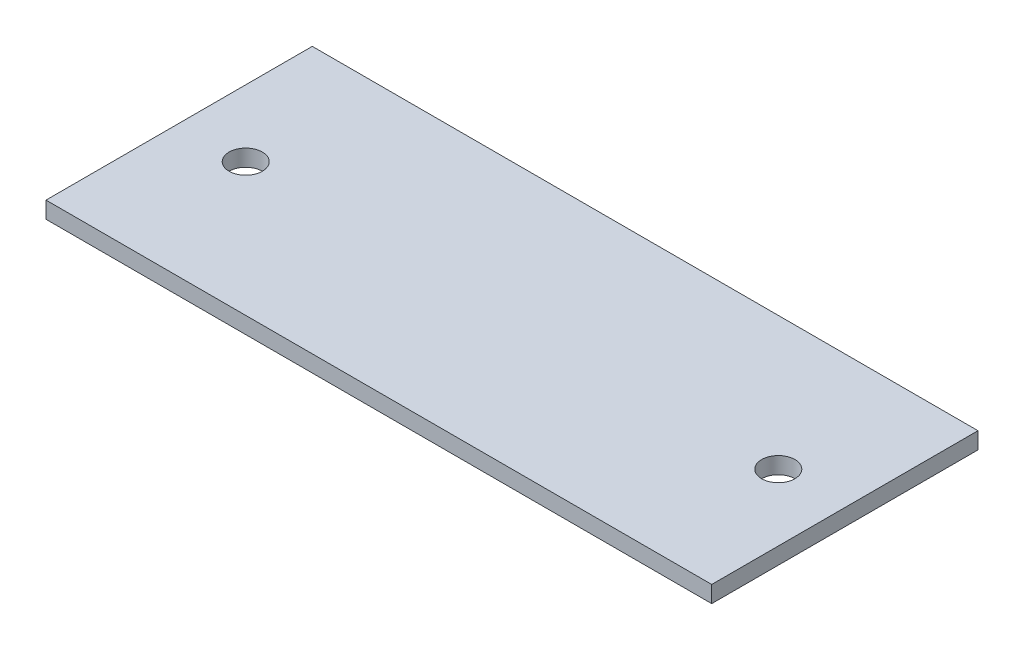
SolidWorks part; units mm, degrees
material "6061 Alloy"
ref_plane "Front Plane" through (0, 0, 0) normal (0, 0, 1) x (1, 0, 0)
ref_plane "Top Plane" through (0, 0, 0) normal (0, 1, 0) x (1, 0, 0)
ref_plane "Right Plane" through (0, 0, 0) normal (1, 0, 0) x (0, 0, -1)
sketch "Sketch1" plane through (0, 0, 0) normal (0, 1, 0) x (1, 0, 0)
  line L1 (0, 0) -> (127, 0)
  line L2 (0, 0) -> (0, 50.8)
  line L3 (0, 50.8) -> (127, 50.8)
  line L4 (127, 0) -> (127, 50.8)
  dimension "D1" = 127
  dimension "D2" = 50.8
extrude "Boss-Extrude1" add sketch "Sketch1" along normal blind 3.175
sketch "Sketch2" plane through (0, 0, 0) normal (0, -1, 0) x (-1, 0, 0)
  line L0 (-127, 0) -> (-127, 50.8) construction
  line L1 (0, 0) -> (-127, 0) construction
  circle A0 centre (-114.3, 25.4) radius 3.175
  circle A1 centre (-12.7, 25.4) radius 3.175
  dimension "D1" = 12.7
  dimension "D2" = 25.4
  dimension "D3" = 25.4
  dimension "D4" = 114.3
extrude "Cut-Extrude1" cut sketch "Sketch2" against normal blind 24.638
